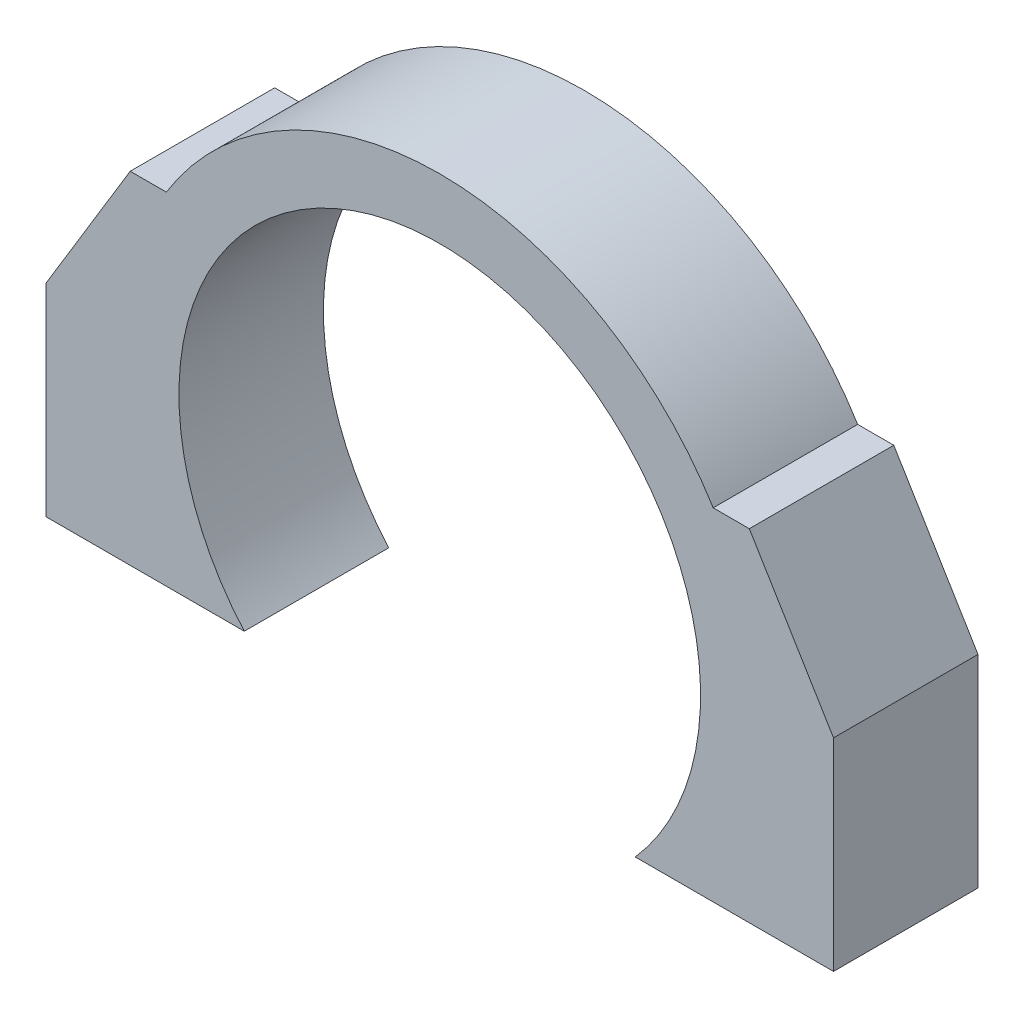
SolidWorks part; units mm, degrees
ref_plane "Plano frontal" through (0, 0, 0) normal (0, 0, 1) x (1, 0, 0)
ref_plane "Plano superior" through (0, 0, 0) normal (0, 1, 0) x (1, 0, 0)
ref_plane "Plano direito" through (0, 0, 0) normal (1, 0, 0) x (0, 0, -1)
sketch "Esboço1" plane through (0, 0, 0) normal (0, 0, 1) x (1, 0, 0)
  line L0 (-27.0555, 0) -> (27.0555, 0) construction
  line L1 (-27.0555, 0) -> (-54.5, 0)
  line L3 (-42.8465, 47.2457) -> (-37.8465, 47.2457)
  line L4 (27.0555, 0) -> (54.5, 0)
  line L5 (54.5, 0) -> (54.5, 28)
  line L6 (42.8465, 47.2457) -> (37.8465, 47.2457)
  line L7 (-42.8465, 47.2457) -> (-54.5, 28)
  line L8 (-54.5, 0) -> (-54.5, 28)
  line L9 (42.8465, 47.2457) -> (54.5, 28)
  arc A0 (-27.0555, 0) -> (27.0555, 0) centre (0, 23.9) cw
  arc A1 (-37.8465, 47.2457) -> (37.8465, 47.2457) centre (0, 23.9) cw
  point P3 (0, 0)
  point P9 (-46.8274, 38.9948)
  point P12 (-39.5, 0)
  point P13 (39.5, 0)
  point P14 (0, 60)
  point P18 (0, 0)
  point P19 (-54.5, 19.625)
  dimension "D1" = 36.1
  dimension "D4" = 44.4677
  dimension "D2" = 79
  dimension "D3" = 39.5
  dimension "D5" = 15
  dimension "D6" = 60
  dimension "D7" = 5
  dimension "D8" = 19.2457
  dimension "D9" = 28
extrude "Ressalto-extrusão1" add sketch "Esboço1" along normal blind 20
